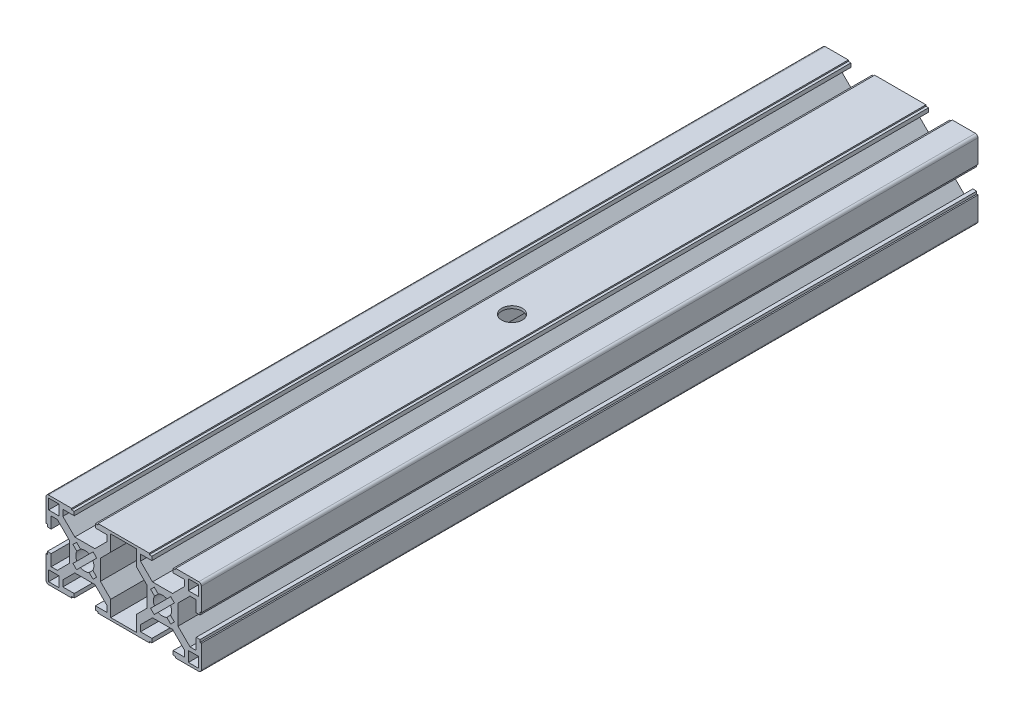
SolidWorks part; units mm, degrees
material "6063-T83"
ref_plane "Plano frontal" through (0, 0, 0) normal (0, 0, 1) x (1, 0, 0)
ref_plane "Plano superior" through (0, 0, 0) normal (0, 1, 0) x (1, 0, 0)
ref_plane "Plano direito" through (0, 0, 0) normal (1, 0, 0) x (0, 0, -1)
sketch "Esboço1" plane through (0, 0, 0) normal (0, 0, 1) x (1, 0, 0)
  line L5 (0, 0) -> (-17.7944, 17.7944) construction
  line L6 (0, 3.5) -> (0, 6)
  line L8 (0, 6) -> (-3.8787, 6)
  line L9 (-3.5, 0) -> (-6, 0)
  line L48 (-6, 0) -> (-6, 3.8787)
  line L49 (-3.8787, 6) -> (-8.5, 10.6213)
  line L50 (-6, 3.8787) -> (-10.6213, 8.5)
  line L51 (0, 0) -> (-12.921, 0) construction
  line L52 (-8.5, 13) -> (-4.1, 13)
  line L53 (-4.1, 13) -> (-4.1, 14.5)
  line L54 (-4.1, 14.5) -> (-5.1, 14.5)
  line L55 (-5.1, 14.5) -> (-5.1, 15)
  line L56 (-5.1, 15) -> (-15, 15)
  line L57 (-15, 5.1) -> (-15, 15)
  line L58 (-14.5, 5.1) -> (-15, 5.1)
  line L59 (-14.5, 4.1) -> (-14.5, 5.1)
  line L60 (-13, 4.1) -> (-14.5, 4.1)
  line L61 (-13, 8.5) -> (-13, 4.1)
  line L62 (-1.6646, 3.0788) -> (-3.182, 4.5962)
  line L63 (-3.0788, 1.6646) -> (-4.5962, 3.182)
  line L64 (-4.5962, 3.182) -> (-3.182, 4.5962)
  line L65 (-8.5, 13) -> (-8.5, 10.6213)
  line L66 (-10, 14) -> (-14, 14)
  line L67 (-10, 14) -> (-10, 10)
  line L68 (-10, 10) -> (-14, 10)
  line L69 (-14, 14) -> (-14, 10)
  line L70 (-10, 14) -> (-14, 10) construction
  line L71 (-10, 10) -> (-14, 14) construction
  line L72 (-13, 8.5) -> (-10.6213, 8.5)
  circle A1 centre (0, 0) radius 3.5
  point P25 (-12, 12)
  dimension "D5" = 10.9
  dimension "D9" = 5.5
  dimension "D10" = 2
  dimension "D11" = 4
  dimension "D12" = 4
  dimension "D13" = 1
  dimension "D1" = 7
  dimension "D2" = 6
  dimension "D3" = 3
  dimension "D4" = 9.9
  dimension "D6" = 0.5
  dimension "D7" = 1.5
  dimension "D8" = 15
  dimension "D14" = 6.5
extrude "Ressalto-extrusão1" add sketch "Esboço1" along normal blind 300 contours A1 L6 L8 L49 L65 L52 L53 L54 L55 L56 L57 L58 L59 L60 L61 L72 L50 L48 L9 L63 L64 L62 L69 L66 L67 L68
sketch "Esboço3" plane through (0, 0, 0) normal (1, 0, 0) x (0, 0, -1)
  line L0 (0, 0) -> (-1000, 0) construction
  dimension "D1" = 1000
pattern_circular "PadrãoCircular1" count 4 over 360 about axis through (0, 0, 0) along (0, 0, 1) of "Ressalto-extrusão1"
pattern_linear "Padrão linear1" count 2 spacing 30 along (1, 0, 0) of "Ressalto-extrusão1", "PadrãoCircular1"
sketch "Esboço4" plane through (0, 0, 0) normal (0, 0, -1) x (-1, 0, 0)
  line L0 (-20, 14) -> (-20, -14)
  line L1 (-20, -14) -> (-10, -14)
  line L2 (-10, -14) -> (-10, 14)
  line L3 (-10, 14) -> (-20, 14)
extrude "Corte-extrusão1" cut sketch "Esboço4" against normal through all
fillet "Filete1" radius 1 4 edges at (45, -15, 150) (45, 15, 150) (-15, 15, 150) (-15, -15, 150)
sketch "Sketch1" plane through (0, 15, 0) normal (0, 1, 0) x (1, 0, 0)
  line L0 (-14, 0) -> (44, -300)
  circle A0 centre (15, -150) radius 4
  dimension "D1" = 8
extrude "Cut-Extrude1" cut sketch "Sketch1" against normal through all contours L0 A0 | L0 A0
